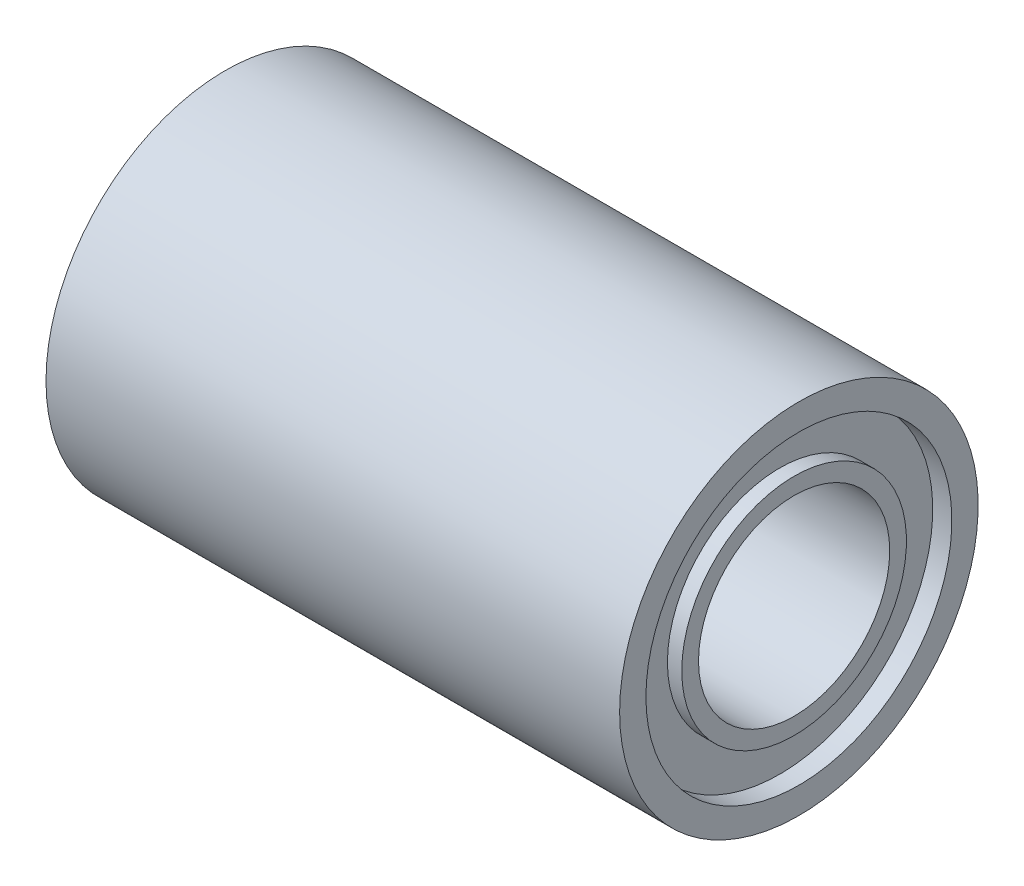
SolidWorks part; units mm, degrees
material "ABS"
ref_plane "Front Plane" through (0, 0, 0) normal (0, 0, 1) x (1, 0, 0)
ref_plane "Top Plane" through (0, 0, 0) normal (0, 1, 0) x (1, 0, 0)
ref_plane "Right Plane" through (0, 0, 0) normal (1, 0, 0) x (0, 0, -1)
sketch "Sketch1" plane through (0, 0, 0) normal (0, 0, 1) x (1, 0, 0)
  line L0 (-30.2753, 0) -> (15, 0) construction
  line L1 (15, -7.5) -> (15, 7.5) construction
  line L2 (0, 11) -> (0, -21.2949) construction
  line L3 (-12, 7.5) -> (12, 7.5)
  line L4 (12, 7.5) -> (12, 6.4)
  line L5 (12, 6.4) -> (11.2, 6.4)
  line L6 (11.2, 6.4) -> (11.2, 4.7)
  line L7 (11.2, 4.7) -> (11.8, 4.7)
  line L8 (11.8, 4.7) -> (11.8, 4)
  line L9 (11.8, 4) -> (-11.8, 4)
  line L10 (-11.8, 4.7) -> (-11.8, 4)
  line L11 (-11.2, 4.7) -> (-11.8, 4.7)
  line L12 (-11.2, 6.4) -> (-11.2, 4.7)
  line L13 (-12, 6.4) -> (-11.2, 6.4)
  line L14 (-12, 7.5) -> (-12, 6.4)
  line L15 (11.8, -4) -> (-11.8, -4) construction
  line L16 (-12, -7.5) -> (12, -7.5) construction
  point P15 (0, 4)
  point P20 (0, 7.5)
  dimension "D1" = 1.1
  dimension "D2" = 0.7
  dimension "D3" = 15
  dimension "D4" = 8
  dimension "D5" = 24
  dimension "D6" = 0.8
  dimension "D7" = 0.6
revolve "Revolve1" add sketch "Sketch1" angle 360 about L0
